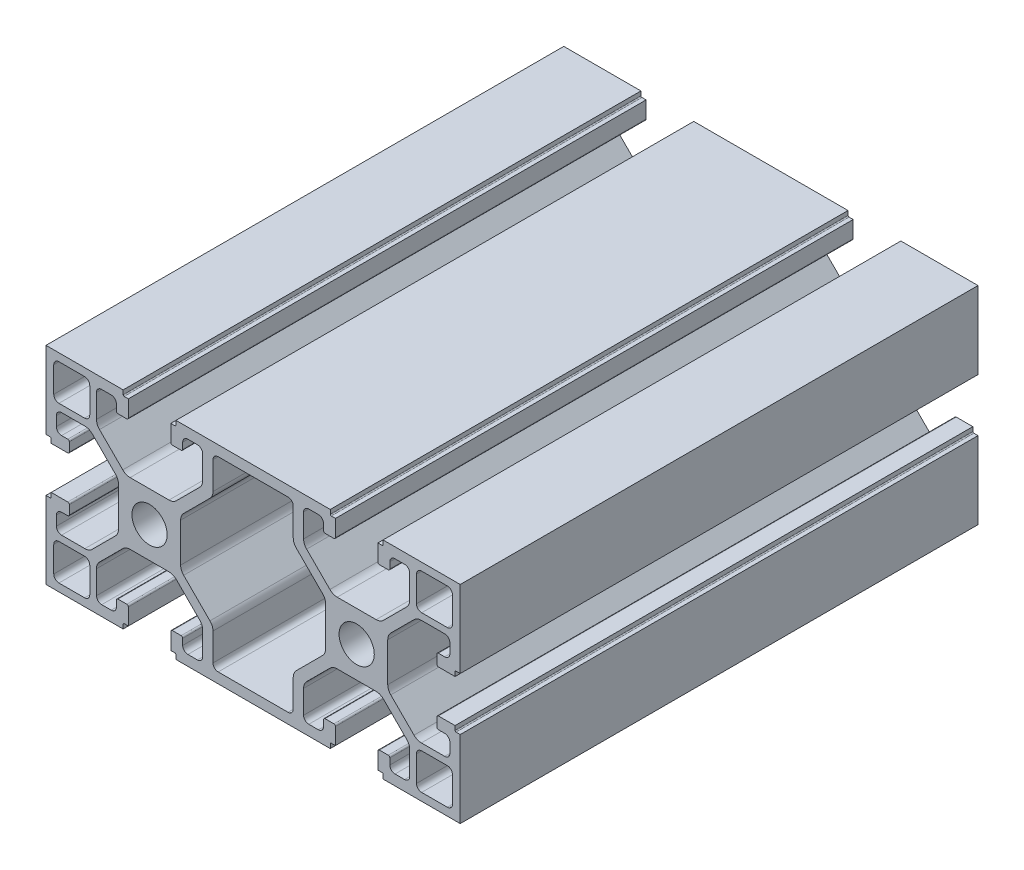
SolidWorks part; units mm, degrees
ref_plane "前视基准面" through (0, 0, 0) normal (0, 0, 1) x (1, 0, 0)
ref_plane "上视基准面" through (0, 0, 0) normal (0, 1, 0) x (1, 0, 0)
ref_plane "右视基准面" through (0, 0, 0) normal (1, 0, 0) x (0, 0, -1)
sketch "草图1" plane through (0, 0, 0) normal (0, 0, 1) x (1, 0, 0)
  line L0 (-24.3716, 18.9402) -> (-39.2716, 18.9402)
  line L1 (-39.2716, 18.9402) -> (-39.2716, 4.0402)
  line L2 (-23.3716, 17.9402) -> (-24.1716, 17.9402)
  line L3 (-24.3716, 18.1402) -> (-24.3716, 18.9402)
  line L4 (-39.2716, 4.0402) -> (-38.4716, 4.0402)
  line L5 (-38.2716, 3.8402) -> (-38.2716, 3.0402)
  line L6 (-31.7642, 9.1902) -> (-36.2716, 9.1902)
  line L7 (-37.2716, 8.1902) -> (-37.2716, 6.3402)
  line L8 (-36.2716, 5.3402) -> (-35.0716, 5.3402)
  line L9 (-34.7716, 5.0402) -> (-34.7716, 3.3402)
  line L10 (-35.0716, 3.0402) -> (-38.2716, 3.0402)
  line L11 (-23.3716, 17.9402) -> (-23.3716, 14.7402)
  line L12 (-23.6716, 14.4402) -> (-25.3716, 14.4402)
  line L13 (-25.6716, 14.7402) -> (-25.6716, 15.9402)
  line L14 (-26.6716, 16.9402) -> (-28.5216, 16.9402)
  line L15 (-29.5216, 15.9402) -> (-29.5216, 11.4328)
  line L16 (-28.9358, 10.0186) -> (-24.4432, 5.526)
  line L17 (-23.0289, 4.9402) -> (-15.5142, 4.9402)
  line L18 (-13.2716, 2.6975) -> (-13.2716, -4.8172)
  line L19 (-15.5142, -7.0598) -> (-23.0289, -7.0598)
  line L20 (-25.2716, -4.8172) -> (-25.2716, 2.6975)
  line L21 (-25.8574, 4.1118) -> (-30.35, 8.6044)
  line L22 (38.2324, 17.4442) -> (33.2784, 17.4442)
  line L23 (-36.7756, 10.4902) -> (-31.8216, 10.4902)
  line L24 (-30.8216, 11.4902) -> (-30.8216, 16.4442)
  line L25 (-31.8216, 17.4442) -> (-36.7756, 17.4442)
  line L26 (38.2324, -19.5638) -> (33.2784, -19.5638)
  line L27 (-15.1716, 17.9402) -> (-14.3716, 17.9402)
  line L28 (-14.1716, 18.1402) -> (-14.1716, 18.9402)
  line L29 (-15.1716, 17.9402) -> (-15.1716, 14.7402)
  line L30 (-14.8716, 14.4402) -> (-13.1716, 14.4402)
  line L31 (-12.8716, 14.7402) -> (-12.8716, 15.9402)
  line L32 (-11.8716, 16.9402) -> (-10.0216, 16.9402)
  line L33 (-9.0216, 15.9402) -> (-9.0216, 11.4328)
  line L34 (-7.0216, 15.9402) -> (-7.0216, 10.6044)
  line L35 (-9.6074, 10.0186) -> (-14.1, 5.526)
  line L36 (-12.6858, 4.1118) -> (-7.6074, 9.1902)
  line L37 (-31.8216, -19.5638) -> (-36.7756, -19.5638)
  line L39 (-23.3716, -20.0598) -> (-24.1716, -20.0598)
  line L40 (-24.3716, -20.2598) -> (-24.3716, -21.0598)
  line L41 (-39.2716, -6.1598) -> (-38.4716, -6.1598)
  line L42 (-38.2716, -5.9598) -> (-38.2716, -5.1598)
  line L43 (-31.7642, -11.3098) -> (-36.2716, -11.3098)
  line L44 (-37.2716, -10.3098) -> (-37.2716, -8.4598)
  line L45 (-36.2716, -7.4598) -> (-35.0716, -7.4598)
  line L46 (-34.7716, -7.1598) -> (-34.7716, -5.4598)
  line L47 (-35.0716, -5.1598) -> (-38.2716, -5.1598)
  line L48 (-23.3716, -20.0598) -> (-23.3716, -16.8598)
  line L49 (-23.6716, -16.5598) -> (-25.3716, -16.5598)
  line L50 (-25.6716, -16.8598) -> (-25.6716, -18.0598)
  line L51 (-26.6716, -19.0598) -> (-28.5216, -19.0598)
  line L52 (-29.5216, -18.0598) -> (-29.5216, -13.5525)
  line L53 (-28.9358, -12.1382) -> (-24.4432, -7.6456)
  line L54 (-25.8574, -6.2314) -> (-30.35, -10.724)
  line L56 (-36.7756, -12.6098) -> (-31.8216, -12.6098)
  line L57 (-30.8216, -13.6098) -> (-30.8216, -18.5638)
  line L60 (-15.1716, -20.0598) -> (-14.3716, -20.0598)
  line L61 (-14.1716, -20.2598) -> (-14.1716, -21.0598)
  line L62 (-15.1716, -20.0598) -> (-15.1716, -16.8598)
  line L63 (-14.8716, -16.5598) -> (-13.1716, -16.5598)
  line L64 (-12.8716, -16.8598) -> (-12.8716, -18.0598)
  line L65 (-11.8716, -19.0598) -> (-10.0216, -19.0598)
  line L66 (-9.0216, -18.0598) -> (-9.0216, -13.5525)
  line L67 (-9.6074, -12.1382) -> (-14.1, -7.6456)
  line L68 (-12.6858, -6.2314) -> (-7.6074, -11.3098)
  line L71 (-37.7756, 11.4902) -> (-37.7756, 16.4442)
  line L73 (-14.1716, 18.9402) -> (0.7284, 18.9402)
  line L74 (-24.3716, -21.0598) -> (-39.2716, -21.0598)
  line L75 (-39.2716, -21.0598) -> (-39.2716, -6.1598)
  line L78 (-37.7756, -13.6098) -> (-37.7756, -18.5638)
  line L80 (-14.1716, -21.0598) -> (0.7284, -21.0598)
  line L81 (15.6284, 18.9402) -> (0.7284, 18.9402)
  line L82 (16.6284, 17.9402) -> (15.8284, 17.9402)
  line L83 (15.6284, 18.1402) -> (15.6284, 18.9402)
  line L84 (16.6284, 17.9402) -> (16.6284, 14.7402)
  line L85 (16.3284, 14.4402) -> (14.6284, 14.4402)
  line L86 (14.3284, 14.7402) -> (14.3284, 15.9402)
  line L87 (13.3284, 16.9402) -> (11.4784, 16.9402)
  line L88 (10.4784, 15.9402) -> (10.4784, 11.4328)
  line L89 (8.4784, 15.9402) -> (8.4784, 10.6044)
  line L90 (11.0642, 10.0186) -> (15.5568, 5.526)
  line L91 (16.9711, 4.9402) -> (24.4858, 4.9402)
  line L92 (26.7284, 2.6975) -> (26.7284, -4.8172)
  line L93 (24.4858, -7.0598) -> (16.9711, -7.0598)
  line L94 (14.7284, -4.8172) -> (14.7284, 2.6975)
  line L95 (14.1426, 4.1118) -> (9.0642, 9.1902)
  line L98 (24.8284, 17.9402) -> (25.6284, 17.9402)
  line L99 (25.8284, 18.1402) -> (25.8284, 18.9402)
  line L100 (40.7284, 4.0402) -> (39.9284, 4.0402)
  line L101 (39.7284, 3.8402) -> (39.7284, 3.0402)
  line L102 (33.2211, 9.1902) -> (37.7284, 9.1902)
  line L103 (38.7284, 8.1902) -> (38.7284, 6.3402)
  line L104 (37.7284, 5.3402) -> (36.5284, 5.3402)
  line L105 (36.2284, 5.0402) -> (36.2284, 3.3402)
  line L106 (36.5284, 3.0402) -> (39.7284, 3.0402)
  line L107 (24.8284, 17.9402) -> (24.8284, 14.7402)
  line L108 (25.1284, 14.4402) -> (26.8284, 14.4402)
  line L109 (27.1284, 14.7402) -> (27.1284, 15.9402)
  line L110 (28.1284, 16.9402) -> (29.9784, 16.9402)
  line L111 (30.9784, 15.9402) -> (30.9784, 11.4328)
  line L112 (30.3926, 10.0186) -> (25.9, 5.526)
  line L113 (27.3142, 4.1118) -> (31.8068, 8.6044)
  line L115 (38.2324, 10.4902) -> (33.2784, 10.4902)
  line L116 (32.2784, 11.4902) -> (32.2784, 16.4442)
  line L119 (16.6284, -20.0598) -> (15.8284, -20.0598)
  line L120 (15.6284, -20.2598) -> (15.6284, -21.0598)
  line L121 (16.6284, -20.0598) -> (16.6284, -16.8598)
  line L122 (16.3284, -16.5598) -> (14.6284, -16.5598)
  line L123 (14.3284, -16.8598) -> (14.3284, -18.0598)
  line L124 (13.3284, -19.0598) -> (11.4784, -19.0598)
  line L125 (10.4784, -18.0598) -> (10.4784, -13.5525)
  line L126 (11.0642, -12.1382) -> (15.5568, -7.6456)
  line L127 (14.1426, -6.2314) -> (9.0642, -11.3098)
  line L130 (24.8284, -20.0598) -> (25.6284, -20.0598)
  line L131 (25.8284, -20.2598) -> (25.8284, -21.0598)
  line L132 (40.7284, -6.1598) -> (39.9284, -6.1598)
  line L133 (39.7284, -5.9598) -> (39.7284, -5.1598)
  line L134 (33.2211, -11.3098) -> (37.7284, -11.3098)
  line L135 (38.7284, -10.3098) -> (38.7284, -8.4598)
  line L136 (37.7284, -7.4598) -> (36.5284, -7.4598)
  line L137 (36.2284, -7.1598) -> (36.2284, -5.4598)
  line L138 (36.5284, -5.1598) -> (39.7284, -5.1598)
  line L139 (24.8284, -20.0598) -> (24.8284, -16.8598)
  line L140 (25.1284, -16.5598) -> (26.8284, -16.5598)
  line L141 (27.1284, -16.8598) -> (27.1284, -18.0598)
  line L142 (28.1284, -19.0598) -> (29.9784, -19.0598)
  line L143 (30.9784, -18.0598) -> (30.9784, -13.5525)
  line L144 (30.3926, -12.1382) -> (25.9, -7.6456)
  line L145 (27.3142, -6.2314) -> (31.8068, -10.724)
  line L147 (38.2324, -12.6098) -> (33.2784, -12.6098)
  line L148 (32.2784, -13.6098) -> (32.2784, -18.5638)
  line L150 (25.8284, 18.9402) -> (40.7284, 18.9402)
  line L153 (39.2324, 11.4902) -> (39.2324, 16.4442)
  line L155 (40.7284, 18.9402) -> (40.7284, 4.0402)
  line L156 (15.6284, -21.0598) -> (0.7284, -21.0598)
  line L157 (25.8284, -21.0598) -> (40.7284, -21.0598)
  line L160 (39.2324, -13.6098) -> (39.2324, -18.5638)
  line L162 (40.7284, -21.0598) -> (40.7284, -6.1598)
  line L164 (-6.0216, 16.9402) -> (7.4784, 16.9402)
  line L165 (-7.0216, -18.0598) -> (-7.0216, -12.724)
  line L166 (8.4784, -18.0598) -> (8.4784, -12.724)
  line L167 (-6.0216, -19.0598) -> (7.4784, -19.0598)
  arc A0 (-24.3716, 18.1402) -> (-24.1716, 17.9402) centre (-24.1716, 18.1402) ccw
  arc A1 (-38.2716, 3.8402) -> (-38.4716, 4.0402) centre (-38.4716, 3.8402) ccw
  arc A2 (-36.2716, 9.1902) -> (-37.2716, 8.1902) centre (-36.2716, 8.1902) ccw
  arc A3 (-37.2716, 6.3402) -> (-36.2716, 5.3402) centre (-36.2716, 6.3402) ccw
  arc A4 (-34.7716, 5.0402) -> (-35.0716, 5.3402) centre (-35.0716, 5.0402) ccw
  arc A5 (-35.0716, 3.0402) -> (-34.7716, 3.3402) centre (-35.0716, 3.3402) ccw
  arc A6 (-23.6716, 14.4402) -> (-23.3716, 14.7402) centre (-23.6716, 14.7402) ccw
  arc A7 (-25.6716, 14.7402) -> (-25.3716, 14.4402) centre (-25.3716, 14.7402) ccw
  arc A8 (-25.6716, 15.9402) -> (-26.6716, 16.9402) centre (-26.6716, 15.9402) ccw
  arc A9 (-28.5216, 16.9402) -> (-29.5216, 15.9402) centre (-28.5216, 15.9402) ccw
  arc A10 (-29.5216, 11.4328) -> (-28.9358, 10.0186) centre (-27.5216, 11.4328) ccw
  arc A11 (-24.4432, 5.526) -> (-23.0289, 4.9402) centre (-23.0289, 6.9402) ccw
  arc A12 (-25.2716, 2.6975) -> (-25.8574, 4.1118) centre (-27.2716, 2.6975) ccw
  circle A13 centre (-19.2716, -1.0598) radius 3.4
  arc A14 (-30.35, 8.6044) -> (-31.7642, 9.1902) centre (-31.7642, 7.1902) ccw
  arc A15 (-37.7756, 11.4902) -> (-36.7756, 10.4902) centre (-36.7756, 11.4902) ccw
  arc A16 (-31.8216, 10.4902) -> (-30.8216, 11.4902) centre (-31.8216, 11.4902) ccw
  arc A17 (-30.8216, 16.4442) -> (-31.8216, 17.4442) centre (-31.8216, 16.4442) ccw
  arc A18 (-14.3716, 17.9402) -> (-14.1716, 18.1402) centre (-14.3716, 18.1402) ccw
  arc A19 (-15.1716, 14.7402) -> (-14.8716, 14.4402) centre (-14.8716, 14.7402) ccw
  arc A20 (-13.1716, 14.4402) -> (-12.8716, 14.7402) centre (-13.1716, 14.7402) ccw
  arc A21 (-11.8716, 16.9402) -> (-12.8716, 15.9402) centre (-11.8716, 15.9402) ccw
  arc A22 (-9.0216, 15.9402) -> (-10.0216, 16.9402) centre (-10.0216, 15.9402) ccw
  arc A23 (-7.6074, 9.1902) -> (-7.0216, 10.6044) centre (-9.0216, 10.6044) ccw
  arc A24 (-9.6074, 10.0186) -> (-9.0216, 11.4328) centre (-11.0216, 11.4328) ccw
  arc A25 (-15.5142, 4.9402) -> (-14.1, 5.526) centre (-15.5142, 6.9402) ccw
  arc A26 (-12.6858, 4.1118) -> (-13.2716, 2.6975) centre (-11.2716, 2.6975) ccw
  arc A27 (-24.1716, -20.0598) -> (-24.3716, -20.2598) centre (-24.1716, -20.2598) ccw
  arc A28 (-38.4716, -6.1598) -> (-38.2716, -5.9598) centre (-38.4716, -5.9598) ccw
  arc A29 (-37.2716, -10.3098) -> (-36.2716, -11.3098) centre (-36.2716, -10.3098) ccw
  arc A30 (-36.2716, -7.4598) -> (-37.2716, -8.4598) centre (-36.2716, -8.4598) ccw
  arc A31 (-35.0716, -7.4598) -> (-34.7716, -7.1598) centre (-35.0716, -7.1598) ccw
  arc A32 (-34.7716, -5.4598) -> (-35.0716, -5.1598) centre (-35.0716, -5.4598) ccw
  arc A33 (-23.3716, -16.8598) -> (-23.6716, -16.5598) centre (-23.6716, -16.8598) ccw
  arc A34 (-25.3716, -16.5598) -> (-25.6716, -16.8598) centre (-25.3716, -16.8598) ccw
  arc A35 (-26.6716, -19.0598) -> (-25.6716, -18.0598) centre (-26.6716, -18.0598) ccw
  arc A36 (-29.5216, -18.0598) -> (-28.5216, -19.0598) centre (-28.5216, -18.0598) ccw
  arc A37 (-28.9358, -12.1382) -> (-29.5216, -13.5525) centre (-27.5216, -13.5525) ccw
  arc A38 (-23.0289, -7.0598) -> (-24.4432, -7.6456) centre (-23.0289, -9.0598) ccw
  arc A39 (-25.8574, -6.2314) -> (-25.2716, -4.8172) centre (-27.2716, -4.8172) ccw
  arc A40 (-31.7642, -11.3098) -> (-30.35, -10.724) centre (-31.7642, -9.3098) ccw
  arc A41 (-36.7756, -12.6098) -> (-37.7756, -13.6098) centre (-36.7756, -13.6098) ccw
  arc A42 (-30.8216, -13.6098) -> (-31.8216, -12.6098) centre (-31.8216, -13.6098) ccw
  arc A43 (-31.8216, -19.5638) -> (-30.8216, -18.5638) centre (-31.8216, -18.5638) ccw
  arc A44 (-14.1716, -20.2598) -> (-14.3716, -20.0598) centre (-14.3716, -20.2598) ccw
  arc A45 (-14.8716, -16.5598) -> (-15.1716, -16.8598) centre (-14.8716, -16.8598) ccw
  arc A46 (-12.8716, -16.8598) -> (-13.1716, -16.5598) centre (-13.1716, -16.8598) ccw
  arc A47 (-12.8716, -18.0598) -> (-11.8716, -19.0598) centre (-11.8716, -18.0598) ccw
  arc A48 (-10.0216, -19.0598) -> (-9.0216, -18.0598) centre (-10.0216, -18.0598) ccw
  arc A49 (-9.0216, -13.5525) -> (-9.6074, -12.1382) centre (-11.0216, -13.5525) ccw
  arc A50 (-14.1, -7.6456) -> (-15.5142, -7.0598) centre (-15.5142, -9.0598) ccw
  arc A51 (-13.2716, -4.8172) -> (-12.6858, -6.2314) centre (-11.2716, -4.8172) ccw
  arc A52 (-7.0216, -12.724) -> (-7.6074, -11.3098) centre (-9.0216, -12.724) ccw
  arc A55 (-36.7756, 17.4442) -> (-37.7756, 16.4442) centre (-36.7756, 16.4442) ccw
  arc A58 (-37.7756, -18.5638) -> (-36.7756, -19.5638) centre (-36.7756, -18.5638) ccw
  arc A59 (15.6284, 18.1402) -> (15.8284, 17.9402) centre (15.8284, 18.1402) ccw
  arc A60 (16.3284, 14.4402) -> (16.6284, 14.7402) centre (16.3284, 14.7402) ccw
  arc A61 (14.3284, 14.7402) -> (14.6284, 14.4402) centre (14.6284, 14.7402) ccw
  arc A62 (14.3284, 15.9402) -> (13.3284, 16.9402) centre (13.3284, 15.9402) ccw
  arc A63 (11.4784, 16.9402) -> (10.4784, 15.9402) centre (11.4784, 15.9402) ccw
  arc A64 (8.4784, 10.6044) -> (9.0642, 9.1902) centre (10.4784, 10.6044) ccw
  arc A65 (8.4784, 15.9402) -> (7.4784, 16.9402) centre (7.4784, 15.9402) ccw
  arc A66 (10.4784, 11.4328) -> (11.0642, 10.0186) centre (12.4784, 11.4328) ccw
  arc A67 (15.5568, 5.526) -> (16.9711, 4.9402) centre (16.9711, 6.9402) ccw
  arc A68 (14.7284, 2.6975) -> (14.1426, 4.1118) centre (12.7284, 2.6975) ccw
  circle A69 centre (20.7284, -1.0598) radius 3.4
  arc A70 (25.6284, 17.9402) -> (25.8284, 18.1402) centre (25.6284, 18.1402) ccw
  arc A71 (39.9284, 4.0402) -> (39.7284, 3.8402) centre (39.9284, 3.8402) ccw
  arc A72 (38.7284, 8.1902) -> (37.7284, 9.1902) centre (37.7284, 8.1902) ccw
  arc A73 (37.7284, 5.3402) -> (38.7284, 6.3402) centre (37.7284, 6.3402) ccw
  arc A74 (36.5284, 5.3402) -> (36.2284, 5.0402) centre (36.5284, 5.0402) ccw
  arc A75 (36.2284, 3.3402) -> (36.5284, 3.0402) centre (36.5284, 3.3402) ccw
  arc A76 (24.8284, 14.7402) -> (25.1284, 14.4402) centre (25.1284, 14.7402) ccw
  arc A77 (26.8284, 14.4402) -> (27.1284, 14.7402) centre (26.8284, 14.7402) ccw
  arc A78 (28.1284, 16.9402) -> (27.1284, 15.9402) centre (28.1284, 15.9402) ccw
  arc A79 (30.9784, 15.9402) -> (29.9784, 16.9402) centre (29.9784, 15.9402) ccw
  arc A80 (30.3926, 10.0186) -> (30.9784, 11.4328) centre (28.9784, 11.4328) ccw
  arc A81 (24.4858, 4.9402) -> (25.9, 5.526) centre (24.4858, 6.9402) ccw
  arc A82 (27.3142, 4.1118) -> (26.7284, 2.6975) centre (28.7284, 2.6975) ccw
  arc A83 (33.2211, 9.1902) -> (31.8068, 8.6044) centre (33.2211, 7.1902) ccw
  arc A84 (38.2324, 10.4902) -> (39.2324, 11.4902) centre (38.2324, 11.4902) ccw
  arc A85 (32.2784, 11.4902) -> (33.2784, 10.4902) centre (33.2784, 11.4902) ccw
  arc A86 (33.2784, 17.4442) -> (32.2784, 16.4442) centre (33.2784, 16.4442) ccw
  arc A87 (15.8284, -20.0598) -> (15.6284, -20.2598) centre (15.8284, -20.2598) ccw
  arc A88 (16.6284, -16.8598) -> (16.3284, -16.5598) centre (16.3284, -16.8598) ccw
  arc A89 (14.6284, -16.5598) -> (14.3284, -16.8598) centre (14.6284, -16.8598) ccw
  arc A90 (13.3284, -19.0598) -> (14.3284, -18.0598) centre (13.3284, -18.0598) ccw
  arc A91 (10.4784, -18.0598) -> (11.4784, -19.0598) centre (11.4784, -18.0598) ccw
  arc A92 (11.0642, -12.1382) -> (10.4784, -13.5525) centre (12.4784, -13.5525) ccw
  arc A93 (16.9711, -7.0598) -> (15.5568, -7.6456) centre (16.9711, -9.0598) ccw
  arc A94 (14.1426, -6.2314) -> (14.7284, -4.8172) centre (12.7284, -4.8172) ccw
  arc A95 (9.0642, -11.3098) -> (8.4784, -12.724) centre (10.4784, -12.724) ccw
  arc A96 (25.8284, -20.2598) -> (25.6284, -20.0598) centre (25.6284, -20.2598) ccw
  arc A97 (39.7284, -5.9598) -> (39.9284, -6.1598) centre (39.9284, -5.9598) ccw
  arc A98 (37.7284, -11.3098) -> (38.7284, -10.3098) centre (37.7284, -10.3098) ccw
  arc A99 (38.7284, -8.4598) -> (37.7284, -7.4598) centre (37.7284, -8.4598) ccw
  arc A100 (36.2284, -7.1598) -> (36.5284, -7.4598) centre (36.5284, -7.1598) ccw
  arc A101 (36.5284, -5.1598) -> (36.2284, -5.4598) centre (36.5284, -5.4598) ccw
  arc A102 (25.1284, -16.5598) -> (24.8284, -16.8598) centre (25.1284, -16.8598) ccw
  arc A103 (27.1284, -16.8598) -> (26.8284, -16.5598) centre (26.8284, -16.8598) ccw
  arc A104 (27.1284, -18.0598) -> (28.1284, -19.0598) centre (28.1284, -18.0598) ccw
  arc A105 (29.9784, -19.0598) -> (30.9784, -18.0598) centre (29.9784, -18.0598) ccw
  arc A106 (30.9784, -13.5525) -> (30.3926, -12.1382) centre (28.9784, -13.5525) ccw
  arc A107 (25.9, -7.6456) -> (24.4858, -7.0598) centre (24.4858, -9.0598) ccw
  arc A108 (26.7284, -4.8172) -> (27.3142, -6.2314) centre (28.7284, -4.8172) ccw
  arc A109 (31.8068, -10.724) -> (33.2211, -11.3098) centre (33.2211, -9.3098) ccw
  arc A110 (39.2324, -13.6098) -> (38.2324, -12.6098) centre (38.2324, -13.6098) ccw
  arc A111 (33.2784, -12.6098) -> (32.2784, -13.6098) centre (33.2784, -13.6098) ccw
  arc A112 (32.2784, -18.5638) -> (33.2784, -19.5638) centre (33.2784, -18.5638) ccw
  arc A115 (39.2324, 16.4442) -> (38.2324, 17.4442) centre (38.2324, 16.4442) ccw
  arc A118 (38.2324, -19.5638) -> (39.2324, -18.5638) centre (38.2324, -18.5638) ccw
  arc A119 (-6.0216, 16.9402) -> (-7.0216, 15.9402) centre (-6.0216, 15.9402) ccw
  arc A120 (-7.0216, -18.0598) -> (-6.0216, -19.0598) centre (-6.0216, -18.0598) ccw
  arc A121 (7.4784, -19.0598) -> (8.4784, -18.0598) centre (7.4784, -18.0598) ccw
extrude "凸台-拉伸1" add sketch "草图1" along normal blind 100
